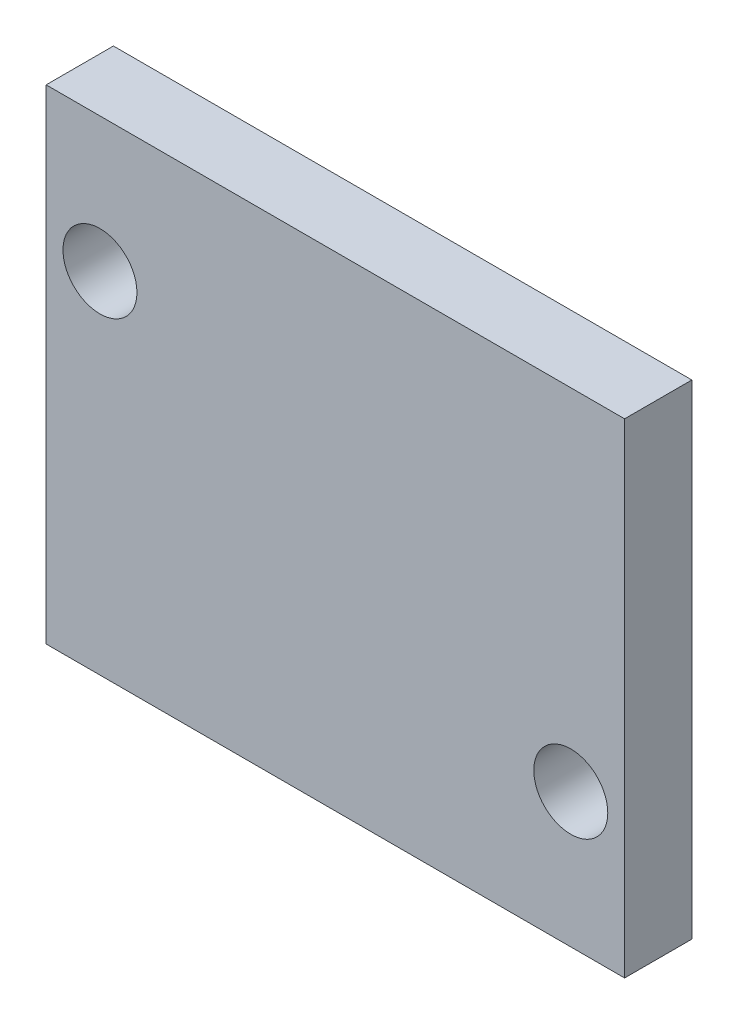
SolidWorks part; units mm, degrees
ref_plane "Ebene vorne" through (0, 0, 0) normal (0, 0, 1) x (1, 0, 0)
ref_plane "Ebene oben" through (0, 0, 0) normal (0, 1, 0) x (1, 0, 0)
ref_plane "Ebene rechts" through (0, 0, 0) normal (1, 0, 0) x (0, 0, -1)
sketch "Skizze1" plane through (0, 0, 0) normal (0, 0, 1) x (1, 0, 0)
  line L0 (4, 26) -> (4, 0) construction
  line L1 (0, 36) -> (43, 36)
  line L2 (0, 36) -> (0, 0)
  line L3 (0, 0) -> (43, 0)
  line L4 (43, 36) -> (43, 0)
  line L5 (4, 0) -> (39, 10) construction
  line L6 (39, 10) -> (39, 36) construction
  line L7 (39, 36) -> (4, 26) construction
  line L8 (43, -33.2886) -> (43, 49.2186) construction
  line L9 (39, 10) -> (43, 10) construction
  line L10 (0, 66.2577) -> (0, -16.2495) construction
  line L11 (4, 26) -> (0, 26) construction
  circle A2 centre (4, 26) radius 2.75
  circle A3 centre (39, 10) radius 2.75
  dimension "D3" = 5.5
  dimension "D1" = 10
  dimension "D2" = 10
  dimension "D4" = 43
  dimension "D5" = 35
  dimension "D6" = 16
extrude "Aufsatz-Linear austragen1" add sketch "Skizze1" along normal blind 5
